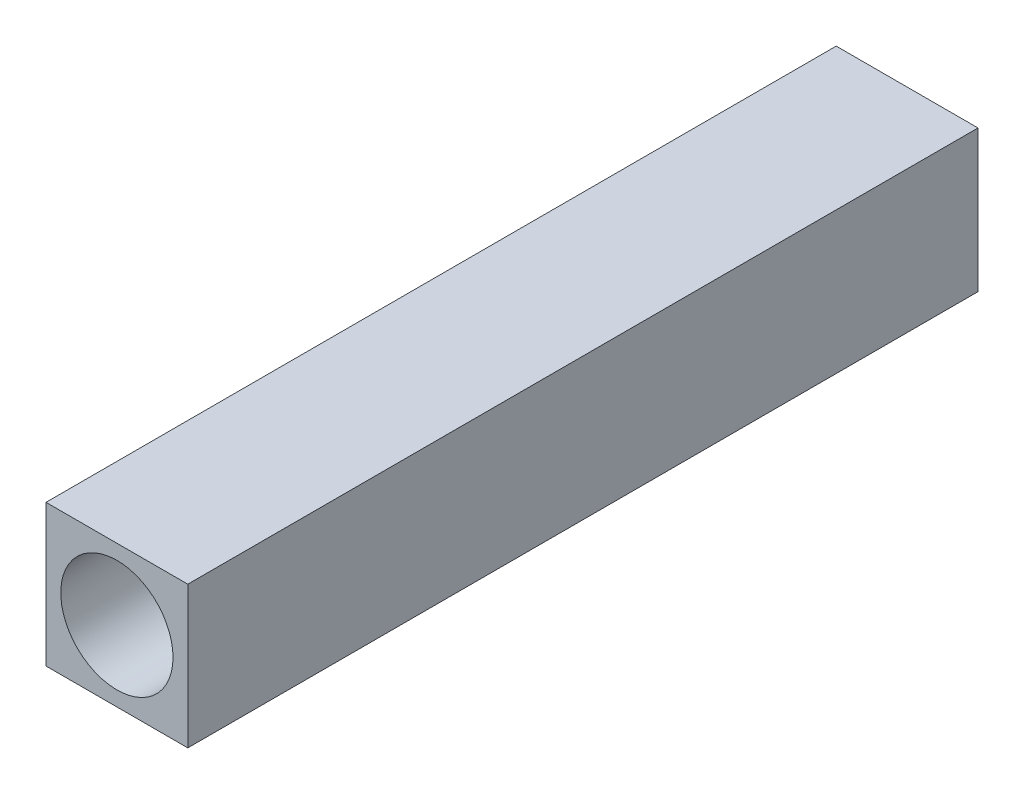
SolidWorks part; units mm, degrees
material "PET"
ref_plane "Front Plane" through (0, 0, 0) normal (0, 0, 1) x (1, 0, 0)
ref_plane "Top Plane" through (0, 0, 0) normal (0, 1, 0) x (1, 0, 0)
ref_plane "Right Plane" through (0, 0, 0) normal (1, 0, 0) x (0, 0, -1)
sketch "Sketch1" plane through (0, 0, 0) normal (0, 0, 1) x (1, 0, 0)
  circle A0 centre (0, 0) radius 9.652
  circle A1 centre (0, 0) radius 12.192
  dimension "D1" = 19.304
  dimension "D2" = 24.384
extrude "Main Inner Tube" add sketch "Sketch1" along normal blind 135.89
sketch "Sketch2" plane through (0, 0, 0) normal (0, 0, -1) x (-1, 0, 0)
  line L1 (-12.192, 12.192) -> (12.192, 12.192)
  line L2 (-12.192, 12.192) -> (-12.192, -12.192)
  line L3 (-12.192, -12.192) -> (12.192, -12.192)
  line L4 (12.192, 12.192) -> (12.192, -12.192)
  circle A0 centre (0, 0) radius 12.192 construction
  circle A1 centre (0, 0) radius 9.652
extrude "Rectangle Outside" add sketch "Sketch2" against normal through all
